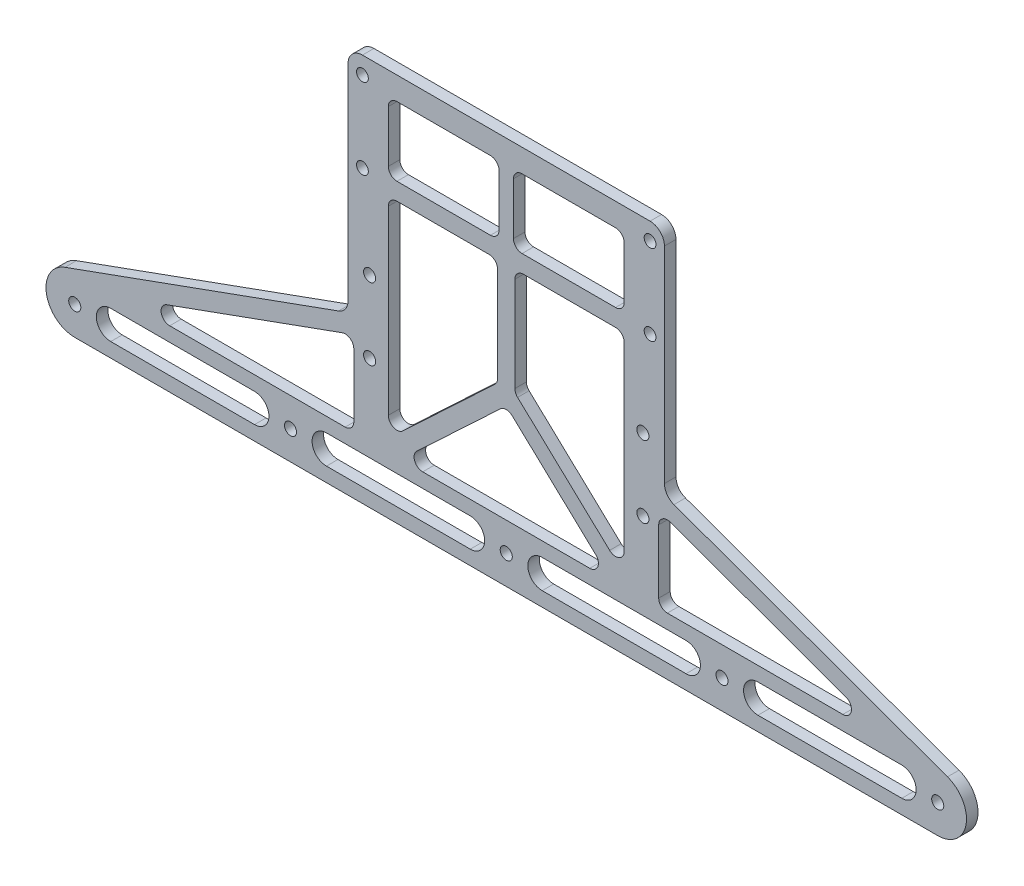
SolidWorks part; units mm, degrees
material "Thornel Mat VMA"
ref_plane "前视基准面" through (0, 0, 0) normal (0, 0, 1) x (1, 0, 0)
ref_plane "上视基准面" through (0, 0, 0) normal (0, 1, 0) x (1, 0, 0)
ref_plane "右视基准面" through (0, 0, 0) normal (1, 0, 0) x (0, 0, -1)
other "Configuration Table"
sketch "草图1" plane through (0, 0, 0) normal (0, 0, 1) x (1, 0, 0)
  line L1 (-55, -20) -> (55, -20)
  line L2 (-55, -20) -> (-55, 20)
  line L3 (-55, 20) -> (55, 20)
  line L4 (55, -20) -> (55, 20)
  line L5 (-55, -20) -> (55, 20) construction
  line L6 (-55, 20) -> (55, -20) construction
  line L7 (-50, -14) -> (50, -14) construction
  line L8 (-50, -14) -> (-50, 14) construction
  line L9 (-50, 14) -> (50, 14) construction
  line L10 (50, -14) -> (50, 14) construction
  line L11 (-50, -14) -> (50, 14) construction
  line L12 (-50, 14) -> (50, -14) construction
  circle A0 centre (-50, 14) radius 2.05
  circle A1 centre (50, 14) radius 2.05
  circle A2 centre (50, -14) radius 2.05
  circle A3 centre (-50, -14) radius 2.05
  point P0 (0, 0)
  point P5 (0, 0)
  dimension "D3" = 4.1
  dimension "D1" = 40
  dimension "D2" = 110
  dimension "D4" = 28
  dimension "D5" = 5
extrude "凸台-拉伸1" add sketch "草图1" along normal blind 4
sketch "草图2" plane through (0, 0, 4) normal (0, 0, 1) x (1, 0, 0)
  line L0 (-55, -60) -> (-207.0406, -115)
  line L1 (-55, -20) -> (55, -20)
  line L2 (-55, -20) -> (-55, -60)
  line L3 (-55, -60) -> (55, -60)
  line L4 (55, -20) -> (55, -60)
  line L5 (-207.0406, -115) -> (207.0406, -115)
  line L6 (207.0406, -115) -> (55, -60)
  line L7 (0, 0) -> (0, -50000) construction
  line L8 (-150, -105) -> (150, -105) construction
  circle A0 centre (-150, -105) radius 10 construction
  circle A1 centre (150, -105) radius 10 construction
  circle A2 centre (-150, -105) radius 2.1
  circle A3 centre (-75, -105) radius 2.1
  circle A4 centre (0, -105) radius 2.1
  circle A5 centre (75, -105) radius 2.1
  circle A6 centre (150, -105) radius 2.1
  line M10 (-55, -20) -> (55, -20)
  dimension "D4" = 10
  dimension "D5" = 4.2
  dimension "D1" = 95
  dimension "D2" = 55
  dimension "D3" = 300
  dimension "D6" = 5
extrude "凸台-拉伸2" add sketch "草图2" against normal up to surface (4 mm away) contours L5 L6 L3 L0 A6 A5 A4 A3 A2 | L4 L2 L3 M10 up to face at (52.05, -14, 0)
fillet "圆角3" radius 10 2 edges at (207.0406, -115, 2) (-207.0406, -115, 2)
fillet "圆角4" radius 5 4 edges at (-55, -60, 2) (-55, 20, 2) (55, -60, 2) (55, 20, 2)
sketch "草图5" plane through (0, 0, 4) normal (0, 0, 1) x (1, 0, 0)
  line L0 (50, 20) -> (-50, 20) construction
  line L1 (-41, -12) -> (41, -12)
  line L2 (-41, -12) -> (-41, 12)
  line L3 (-41, 12) -> (41, 12)
  line L4 (41, -12) -> (41, 12)
  line L5 (-41, -12) -> (41, 12) construction
  line L6 (-41, 12) -> (41, -12) construction
  line L7 (-2.5, 12) -> (-2.5, -12)
  line L8 (2.5, 12) -> (2.5, -12)
  line L9 (0, 0) -> (0, -50000) construction
  line L11 (-41, -18) -> (-41, -95)
  line L12 (-41, -18) -> (41, -18)
  line L13 (41, -18) -> (41, -95)
  line L14 (41, -95) -> (-41, -95)
  line L15 (41, -18) -> (-41, -95) construction
  line L16 (-41, -18) -> (41, -95) construction
  line L17 (36.6174, -18) -> (-41, -90.8847)
  line L18 (-41, -22.1153) -> (36.6174, -95)
  line L19 (41, -22.1153) -> (-36.6174, -95)
  line L20 (-36.6174, -18) -> (41, -90.8847)
  line L21 (-38.9464, -15.8131) -> (43.0536, -92.8131) construction
  line L22 (-43.0536, -20.1869) -> (38.9464, -97.1869) construction
  line L23 (38.9464, -15.8131) -> (-43.0536, -92.8131) construction
  line L24 (43.0536, -20.1869) -> (-38.9464, -97.1869) construction
  line L25 (-3, -18) -> (-3, -95)
  line L26 (3, -18) -> (3, -95)
  circle A0 centre (50, 14) radius 2.05 construction
  circle A2 centre (-150, -105) radius 10
  arc A3 (-153.4017, -95.5964) -> (-150, -115) centre (-150, -105) ccw construction
  point P0 (0, 0)
  dimension "D5" = 3
  dimension "D1" = 8
  dimension "D2" = 9
  dimension "D3" = 5
  dimension "D4" = 6
  dimension "D7" = 6
  dimension "D6" = 3
extrude "切除-拉伸3" cut sketch "草图5" against normal blind 10 contours L7 L3 L2 L1 | L3 L8 L1 L4 | L25 L12 L20 | L25 L20 L12 L11 L18 L17 | L18 L11 L17 | L12 L26 L17 | L17 L26 L20 L19 L13 L12 | L19 L20 L13 | L18 L26 L14 | L25 L19 L14
sketch "草图6" plane through (0, 0, 4) normal (0, 0, 1) x (1, 0, 0)
  line L0 (-150, -105) -> (-75, -105) construction
  line L1 (-75, -105) -> (0, -105) construction
  line L2 (0, -105) -> (75, -105) construction
  line L3 (75, -105) -> (150, -105) construction
  line L4 (-137.5, -105) -> (-87.5, -105) construction
  line L5 (-137.5, -100) -> (-87.5, -100)
  line L6 (-137.5, -110) -> (-87.5, -110)
  line L7 (-62.5, -105) -> (-12.5, -105) construction
  line L8 (-62.5, -100) -> (-12.5, -100)
  line L9 (-62.5, -110) -> (-12.5, -110)
  line L10 (12.5, -105) -> (62.5, -105) construction
  line L11 (12.5, -100) -> (62.5, -100)
  line L12 (12.5, -110) -> (62.5, -110)
  line L13 (87.5, -105) -> (137.5, -105) construction
  line L14 (87.5, -100) -> (137.5, -100)
  line L15 (87.5, -110) -> (137.5, -110)
  line L18 (-53, -65.657) -> (-134.115, -95)
  line L19 (-134.115, -95) -> (-53, -95)
  line L20 (-53, -95) -> (-53, -65.657)
  line L21 (-58.2991, -61.1934) -> (-153.4017, -95.5964) construction
  line L22 (-41, -18) -> (-41, -90.8847) construction
  line L23 (0, 0) -> (0, -50000) construction
  line L24 (134.115, -95) -> (53, -95)
  line L25 (53, -65.657) -> (134.115, -95)
  line L26 (53, -95) -> (53, -65.657)
  arc A0 (-137.5, -100) -> (-137.5, -110) centre (-137.5, -105) ccw
  arc A1 (-87.5, -110) -> (-87.5, -100) centre (-87.5, -105) ccw
  arc A2 (-62.5, -100) -> (-62.5, -110) centre (-62.5, -105) ccw
  arc A3 (-12.5, -110) -> (-12.5, -100) centre (-12.5, -105) ccw
  arc A4 (12.5, -100) -> (12.5, -110) centre (12.5, -105) ccw
  arc A5 (62.5, -110) -> (62.5, -100) centre (62.5, -105) ccw
  arc A6 (87.5, -100) -> (87.5, -110) centre (87.5, -105) ccw
  arc A7 (137.5, -110) -> (137.5, -100) centre (137.5, -105) ccw
  point P14 (-112.5, -105)
  point P20 (-37.5, -105)
  point P27 (37.5, -105)
  point P34 (112.5, -105)
  dimension "D1" = 5
  dimension "D2" = 50
  dimension "D3" = 6
  dimension "D4" = 12
  dimension "D5" = 10
extrude "切除-拉伸4" cut sketch "草图6" against normal blind 10
sketch "草图7" plane through (0, 0, 4) normal (0, 0, 1) x (1, 0, 0)
  line L0 (-3, -95) -> (3, -95)
  line L1 (3, -95) -> (3, -63.4324)
  line L2 (3, -63.4324) -> (0, -60.6153)
  line L3 (0, -60.6153) -> (-3, -63.4324)
  line L4 (-3, -63.4324) -> (-3, -95)
  line L5 (-3, -63.4324) -> (-36.6174, -95) construction
  line L6 (3, -63.4324) -> (36.6174, -95) construction
extrude "切除-拉伸5" cut sketch "草图7" against normal blind 10
fillet "圆角5" radius 3 25 edges at (41, -90.8847, 2) (3, -55.2017, 2) (3, -18, 2) (41, -18, 2) (-41, -90.8847, 2) (-3, -18, 2) (-3, -55.2017, 2) (41, -12, 2) (2.5, -12, 2) (2.5, 12, 2) (41, 12, 2) (-41, -12, 2) (-41, 12, 2) (-2.5, 12, 2) (-2.5, -12, 2) (134.115, -95, 2) (53, -95, 2) (53, -65.657, 2) (-53, -95, 2) (-134.115, -95, 2) (-53, -65.657, 2) (36.6174, -95, 2) (-36.6174, -95, 2) (0, -60.6153, 2) (-41, -18, 2)
sketch "草图8" plane through (0, 0, 4) normal (0, 0, 1) x (1, 0, 0)
  line L0 (-150, -115) -> (150, -115) construction
  line L1 (-47.5, -70) -> (47.5, -70) construction
  line L2 (-47.5, -70) -> (-47.5, -45) construction
  line L3 (-47.5, -45) -> (47.5, -45) construction
  line L4 (47.5, -70) -> (47.5, -45) construction
  line L5 (-47.5, -70) -> (47.5, -45) construction
  line L6 (-47.5, -45) -> (47.5, -70) construction
  line L7 (0, 0) -> (0, -57.5) construction
  circle A0 centre (-47.5, -45) radius 2.1
  circle A1 centre (-47.5, -70) radius 2.1
  circle A2 centre (47.5, -45) radius 2.1
  circle A3 centre (47.5, -70) radius 2.1
  point P0 (0, -57.5)
  dimension "D4" = 4.2
  dimension "D1" = 45
  dimension "D2" = 25
  dimension "D3" = 95
extrude "切除-拉伸6" cut sketch "草图8" against normal blind 10
